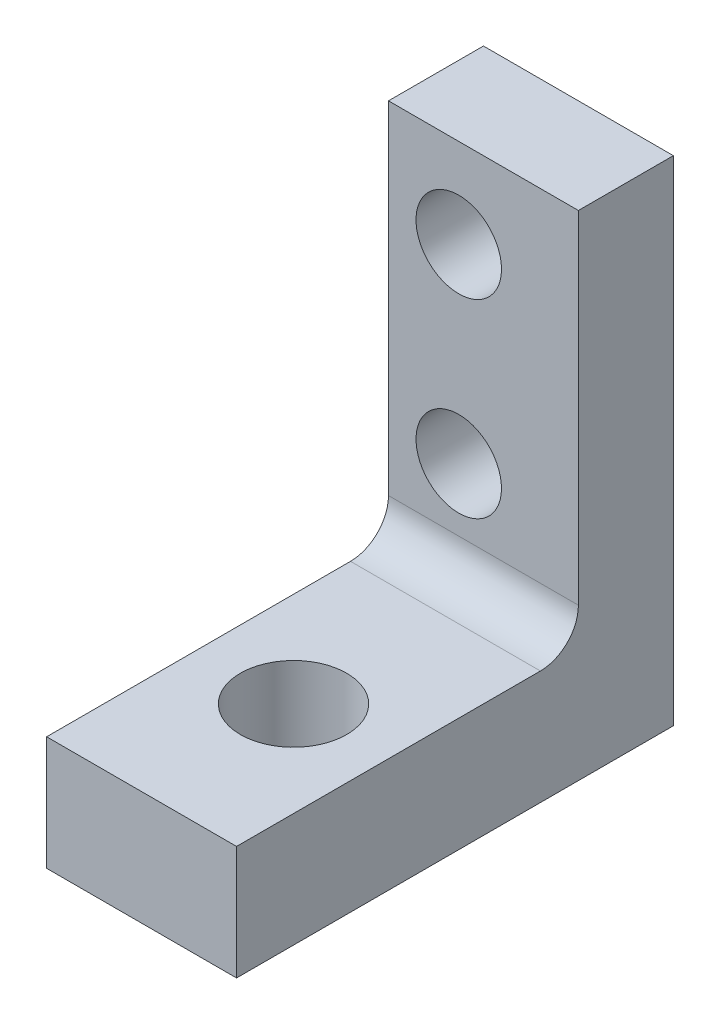
SolidWorks part; units mm, degrees
ref_plane "Front Plane" through (0, 0, 0) normal (0, 0, 1) x (1, 0, 0)
ref_plane "Top Plane" through (0, 0, 0) normal (0, 1, 0) x (1, 0, 0)
ref_plane "Right Plane" through (0, 0, 0) normal (1, 0, 0) x (0, 0, -1)
sketch "Sketch1" plane through (0, 0, 0) normal (0, 1, 0) x (1, 0, 0)
  line L0 (-5, 15) -> (-5, -8)
  line L5 (-5, -8) -> (5, -8)
  line L6 (5, -8) -> (5, 15)
  line L7 (5, 15) -> (-5, 15)
  circle A0 centre (0, 0) radius 2.8
  point P0 (0, 0)
  dimension "D3" = 5.6
  dimension "D1" = 10
  dimension "D2" = 5
  dimension "D4" = 0
  dimension "D5" = 8
  dimension "D6" = 15
extrude "Boss-Extrude1" add sketch "Sketch1" along normal blind 6 contours L0 L5 L6 L7 | A0
sketch "Sketch2" plane through (0, 6, 0) normal (0, 1, 0) x (1, 0, 0)
  line L0 (-5, 15) -> (5, 15)
  line L1 (5, 15) -> (-5, 15) construction
  line L2 (5, 15) -> (5, 10)
  line L3 (5, -8) -> (5, 15) construction
  line L4 (5, 10) -> (-5, 10)
  line L5 (-5, 15) -> (-5, -8) construction
  line L6 (-5, 10) -> (-5, 15)
  dimension "D1" = 5
extrude "Boss-Extrude2" add sketch "Sketch2" along normal blind 20
sketch "Sketch4" plane through (0, 0, -10) normal (0, 0, 1) x (1, 0, 0)
  line L0 (-5, 6) -> (5, 6) construction
  line L1 (-5, 26) -> (-5, 6) construction
  circle A0 centre (-1.3, 11.3) radius 2.25
  circle A1 centre (-1.3, 21.3) radius 2.25
  dimension "D2" = 4.5
  dimension "D1" = 5.3
  dimension "D3" = 3.7
  dimension "D4" = 2
extrude "Cut-Extrude1" cut sketch "Sketch4" against normal blind 10
fillet "Fillet1" radius 2 1 edges at (0, 6, -10)
